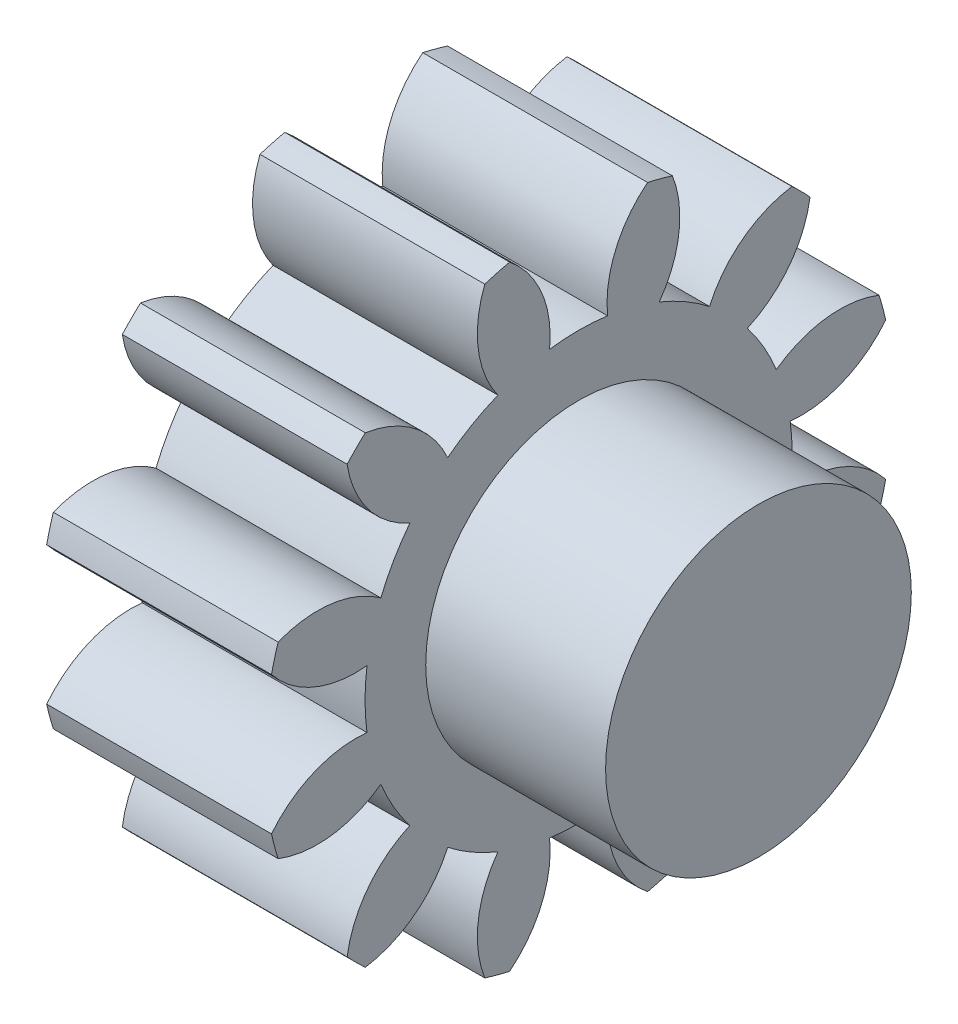
SolidWorks part; units mm, degrees
ref_plane "Plane1" through (0, 0, 0) normal (0, 0, 1) x (1, 0, 0)
ref_plane "Plane2" through (0, 0, 0) normal (0, 1, 0) x (1, 0, 0)
ref_plane "Plane3" through (0, 0, 0) normal (1, 0, 0) x (0, 0, -1)
sketch "HoldingSke" plane through (0, 0, 0) normal (0, 1, 0) x (1, 0, 0)
  line L0 (0, 0) -> (0.3913, -0.0832)
  line L1 (-15, 0) -> (100, 0) construction
  line L2 (0, 0) -> (-2.1039, 2.3779)
  line L3 (0, 0) -> (-11.863, 4.5341)
  line L4 (0, 0) -> (8.4473, 1.7955)
  line L5 (0, 0) -> (-46.8476, -17.4728)
  line L6 (0, 0) -> (-10.362, -6.9913)
  line L7 (-2.1039, 2.3779) -> (8.6586, 51.2059)
  line L8 (-76.2, 54.61) -> (-76, 54.61)
  line L9 (-67.7845, 28.3722) -> (-49.3413, 33.142)
  line L10 (-76.2, 71.12) -> (104.1128, 71.12)
  line L11 (0, 0) -> (-12.5, 0)
  line L12 (-76.2, 101.6) -> (-76.113, 101.6)
  line L13 (24.9733, 27.94) -> (52.9518, 28.4284)
  line L14 (24.9733, 27.94) -> (24.9743, 27.94)
  line L15 (24.9733, 27.94) -> (100.4006, 29.5858)
  line L16 (-63.627, -2.5) -> (-12.827, -2.5)
  circle A0 centre (0, 0) radius 0.75
  circle A1 centre (0, 0) radius 11.874
  circle A2 centre (0, 0) radius 37.5
  circle A3 centre (0, 0) radius 0.75
  dimension "MHD" = 23.748
  dimension "Hub_dia" = 75
  dimension "Bore" = 1.5
  dimension "MBD" = 1.5
  dimension "Num_teeth" = 12
  dimension "Pitch" = 0.4
  dimension "Overall_len" = 50
  dimension "Show_teeth" = 12
  dimension "Thickness" = 12.5
  dimension "OAL" = 50.0001
  dimension "T_dim" = 0.2
  dimension "Ap" = 14.5
  dimension "H" = 19.05
  dimension "Pitch_radius" = 180.3128
  dimension "Width" = 12.5
  dimension "Backlash" = 0.087
  dimension "Addendum_fac" = 1
  dimension "Dedendum_fac" = 1.25
  dimension "Clearance_fac" = 0.25
  dimension "Dedendum_add" = 0.001
  dimension "Module" = 2.5
sketch "BasProSke" plane through (0, 0, 0) normal (0, 1, 0) x (1, 0, 0)
  line L0 (-10, 0) -> (60, 0) construction
  line L1 (0, 0) -> (0, 17.5)
  line L2 (0, 0) -> (12.5, 0)
  line L3 (12.5, 0) -> (12.5, 17.5)
  line L4 (12.5, 17.5) -> (0, 17.5)
  dimension "Thickness" = 12.5
  dimension "Diameter" = 35
revolve "Base-Revolve" add sketch "BasProSke" angle 360 about L0
sketch "TooCutSke" plane through (0, 0, 0) normal (1, 0, 0) x (0, 0, -1)
  line L1 (0, 0) -> (0, 107) construction
  line L2 (0, 0) -> (-2.1099, 14.8509) construction
  line L3 (0, 0) -> (-7.7081, 28.7671) construction
  line L4 (-2.1099, 14.8509) -> (-3.8541, 14.3835) construction
  arc A0 (1.613, 11.7639) -> (-1.613, 11.7639) centre (0, 0) ccw
  arc A1 (3.8612, 17.0948) -> (-3.8612, 17.0948) centre (0, 0) ccw
  circle A2 centre (0, 0) radius 15 construction
  circle A3 centre (0, 0) radius 14.5222 construction
  arc A4 (-1.613, 11.7639) -> (-3.8612, 17.0948) centre (-7.5806, 12.3867) ccw
  arc A5 (3.8612, 17.0948) -> (1.613, 11.7639) centre (7.5806, 12.3867) ccw
  dimension "Root_dia" = 23.748
  dimension "Overcut_dia" = 35.0508
  dimension "Pitch_dia" = 30
  dimension "Base_dia" = 29.0444
  dimension "Flank_rad" = 6
  dimension "Half_ang" = 15
  dimension "Half_CT" = 1.8056
extrude "ToothCut" cut sketch "TooCutSke" along normal through all
fillet "Breaks" [suppressed] radius 0.05
fillet "RootFillets" [suppressed] radius 0.626
pattern_circular "TeethCuts" count 12 every 30 about axis through (-10, 0, 0) along (1, 0, 0) of "ToothCut", "RootFillets", "Breaks"
sketch "HubNeaOneSke" plane through (0, 0, 0) normal (-1, 0, 0) x (0, 0, 1)
  circle A0 centre (0, 0) radius 11.874
  dimension "Diameter" = 23.748
extrude "HubNearOne" [suppressed] add sketch "HubNeaOneSke" along normal blind 37.5001
sketch "HubNeaBotSke" plane through (0, 0, 0) normal (-1, 0, 0) x (0, 0, 1)
  circle A0 centre (0, 0) radius 11.874
  dimension "Diameter" = 23.748
extrude "HubNearBoth" [suppressed] add sketch "HubNeaBotSke" along normal blind 18.75
ref_plane "FarPln" through (12.5, 0, 0) normal (1, 0, 0) x (0, 0, -1)
sketch "HubFarSke" plane through (12.5, 0, 0) normal (1, 0, 0) x (0, 0, -1)
  circle A0 centre (0, 0) radius 11.874
  dimension "Diameter" = 23.748
extrude "HubFar" [suppressed] add sketch "HubFarSke" along normal blind 18.75
sketch "BorSke" plane through (0, 0, 0) normal (1, 0, 0) x (0, 0, -1)
  circle A0 centre (0, 0) radius 0.75
  dimension "Diameter" = 1.5
extrude "Bore" cut sketch "BorSke" along normal mid plane 100.0001
sketch "KeySke" plane through (0, 0, 0) normal (1, 0, 0) x (0, 0, -1)
  line L0 (-0.3, 0) -> (-0.3, 0.95)
  line L1 (-0.3, 0.95) -> (0.3, 0.95)
  line L2 (0.3, 0.95) -> (0.3, 0)
  line L3 (0, 0) -> (0, 34) construction
  line L4 (-0.3, 0) -> (0.3, 0)
  dimension "Offset" = 0.95
  dimension "Width" = 0.6
extrude "Keyway" [suppressed] cut sketch "KeySke" along normal mid plane 100.0001
pattern_circular "Keyway2" [suppressed] count 2 every 90 about axis through (-10, 0, 0) along (1, 0, 0)
sketch "Esquisse1" plane through (12.5, 0, 0) normal (1, 0, 0) x (0, 0, -1)
  circle A0 centre (0, 0) radius 5
  dimension "D1" = 10
extrude "Enlèv. mat.-Extru.2" cut sketch "Esquisse1" against normal blind 60 and the other way blind 10 contours A0
sketch "Esquisse2" plane through (12.5, 0, 0) normal (1, 0, 0) x (0, 0, -1)
  circle A0 centre (0, 0) radius 8.5
extrude "Boss.-Extru.1" add sketch "Esquisse2" along normal blind 10
equation "' \"Module@HoldingSke\" = 6.35"
equation "' \"Num_teeth@HoldingSke\" = 12"
equation "' \"Ap@HoldingSke\" =  20"
equation "' \"Ap@HoldingSke\" = 20"
equation "' \"Width@HoldingSke\" = 0.5 * 25.4"
equation "' \"Hub_dia@HoldingSke\"= 1 * 25.4"
equation "' \"Hub_dia@HoldingSke\" = 1 * 25.4"
equation "' \"Overall_len@HoldingSke\" = 1.0 * 25.4"
equation "' \"Bore@HoldingSke\" = 0.75 * 25.4"
equation "' \"T_dim@HoldingSke\" = 0.1 * 25.4"
equation "' \"Width@KeySke\" = 0.25 * 25.4"
equation "' \"Show_teeth@HoldingSke\" = 13"
equation "' \"Backlash@HoldingSke\" = 0.009 * 25.4"
equation "' \"Addendum_fac@HoldingSke\" = 1.0"
equation "' \"Dedendum_fac@HoldingSke\" = 1.25"
equation "' \"Dedendum_add@HoldingSke\" = 0.00005 * 25.4"
equation "' \"Clearance_fac@HoldingSke\" = 0.25"
equation "\"Pitch@HoldingSke\" = 1 / \"Module@HoldingSke\""
equation "\"Overcut_dia@TooCutSke\" = (\"Num_teeth@HoldingSke\" + 2 * \"Addendum_fac@HoldingSke\") / \"Pitch@HoldingSke\" + 0.002 * 25.4"
equation "\"Pitch_dia@TooCutSke\" = \"Num_teeth@HoldingSke\" / \"Pitch@HoldingSke\""
equation "\"Base_dia@TooCutSke\" = \"Num_teeth@HoldingSke\" / \"Pitch@HoldingSke\" * cos((\"Ap@HoldingSke\"  * 3.14159265 / 180))"
equation "\"Root_dia@TooCutSke\" = (\"Num_teeth@HoldingSke\" + 2) / \"Pitch@HoldingSke\" - 2 * (\"Addendum_fac@HoldingSke\" + \"Dedendum_fac@HoldingSke\") / \"Pitch@HoldingSke\" - \"Dedendum_add@HoldingSke\" * 2"
equation "\"Half_ang@TooCutSke\" = 180 / \"Num_teeth@HoldingSke\""
equation "\"Half_CT@TooCutSke\" = \"Num_teeth@HoldingSke\" / \"Pitch@HoldingSke\" * sin((3.14159265 / 2 / \"Num_teeth@HoldingSke\")) / 2 - 7 * \"Backlash@HoldingSke\" / 4"
equation "\"Flank_rad@TooCutSke\" = \"Num_teeth@HoldingSke\" / \"Pitch@HoldingSke\" / 5"
equation "\"Radius@RootFillets\" = \"Clearance_fac@HoldingSke\" / \"Pitch@HoldingSke\" + \"Dedendum_add@HoldingSke\""
equation "\"Break_rad@Breaks\" = 0.02 / \"Pitch@HoldingSke\""
equation "\"Thickness@HoldingSke\" = \"Width@HoldingSke\""
equation "\"OAL@HoldingSke\" = \"Thickness@HoldingSke\""
equation "\"MHD@HoldingSke\" = (\"Num_teeth@HoldingSke\" + 2) / \"Pitch@HoldingSke\" - 2 * (\"Addendum_fac@HoldingSke\" + \"Dedendum_fac@HoldingSke\")  / \"Pitch@HoldingSke\" - \"Dedendum_add@HoldingSke\" * 2"
equation "\"MBD@HoldingSke\" = (\"Num_teeth@HoldingSke\" + 2) / \"Pitch@HoldingSke\" - 2 * (\"Addendum_fac@HoldingSke\" + \"Dedendum_fac@HoldingSke\")  / \"Pitch@HoldingSke\" - \"Dedendum_add@HoldingSke\" * 2 - 0.002 * 25.4"
equation "\"MHD@HoldingSke\" = ((sgn( \"MHD@HoldingSke\" - \"Hub_dia@HoldingSke\" )-1)*( \"MHD@HoldingSke\" - \"Hub_dia@HoldingSke\" ))/-2+ \"Hub_dia@HoldingSke\""
equation "\"MBD@HoldingSke\" = ((sgn( \"MBD@HoldingSke\" - \"Bore@HoldingSke\" )-1)*( \"MBD@HoldingSke\" - \"Bore@HoldingSke\" ))/-2+ \"Bore@HoldingSke\""
equation "\"OAL@HoldingSke\" = ((sgn( \"OAL@HoldingSke\" - \"Overall_len@HoldingSke\" )+1)*( \"OAL@HoldingSke\" - \"Overall_len@HoldingSke\" ))/2 + \"Overall_len@HoldingSke\" + 0.000002 * 25.4"
equation "\"Num_teeth@TeethCuts\" = int( \"Show_teeth@HoldingSke\" ) + 1"
equation "\"Num_teeth@TeethCuts\" = ((sgn( \"Num_teeth@TeethCuts\" - \"Num_teeth@HoldingSke\" )-1)*( \"Num_teeth@TeethCuts\" - \"Num_teeth@HoldingSke\" ))/-2+ \"Num_teeth@HoldingSke\""
equation "\"Num_teeth@TeethCuts\" = ((sgn( \"Num_teeth@TeethCuts\" - 2.0)+1)*( \"Num_teeth@TeethCuts\" - 2.0))/2 +2.0"
equation "\"Angle@TeethCuts\" = 360.0 / \"Num_teeth@HoldingSke\""
equation "\"Diameter@BasProSke\" = (\"Num_teeth@HoldingSke\" + 2 * \"Addendum_fac@HoldingSke\") / \"Pitch@HoldingSke\""
equation "\"Thickness@BasProSke\"  = \"Thickness@HoldingSke\""
equation "' \"Fillet_rad@BasProSke\" =  \"Thickness@HoldingSke\" * 0.05"
equation "' \"Fillet_rad@BasProSke\" = \"Thickness@HoldingSke\" * 0.05"
equation "\"MHD@HoldingSke\" = ((sgn( \"MHD@HoldingSke\" - \"Root_dia@TooCutSke\" )-1)*( \"MHD@HoldingSke\" - \"Root_dia@TooCutSke\" ))/-2+ \"Root_dia@TooCutSke\""
equation "\"Diameter@HubNeaOneSke\" = \"MHD@HoldingSke\""
equation "\"Length@HubNearOne\" = \"OAL@HoldingSke\" - \"Thickness@BasProSke\""
equation "\"Diameter@HubNeaBotSke\" = \"MHD@HoldingSke\""
equation "\"Length@HubNearBoth\" = ( \"OAL@HoldingSke\" - \"Thickness@BasProSke\" ) / 2.0"
equation "\"Thickness@FarPln\" = \"Thickness@BasProSke\""
equation "\"Diameter@HubFarSke\" = \"MHD@HoldingSke\""
equation "\"Length@HubFar\" = ( \"OAL@HoldingSke\" - \"Thickness@BasProSke\" ) / 2.0"
equation "\"Diameter@BorSke\" = \"MBD@HoldingSke\""
equation "\"D1@Bore\" = \"OAL@HoldingSke\" * 2.0"
equation "\"D1@Keyway\" = \"OAL@HoldingSke\" * 2.0"
equation "\"Offset@KeySke\" = \"T_dim@HoldingSke\" + \"MBD@HoldingSke\" / 2.0"
